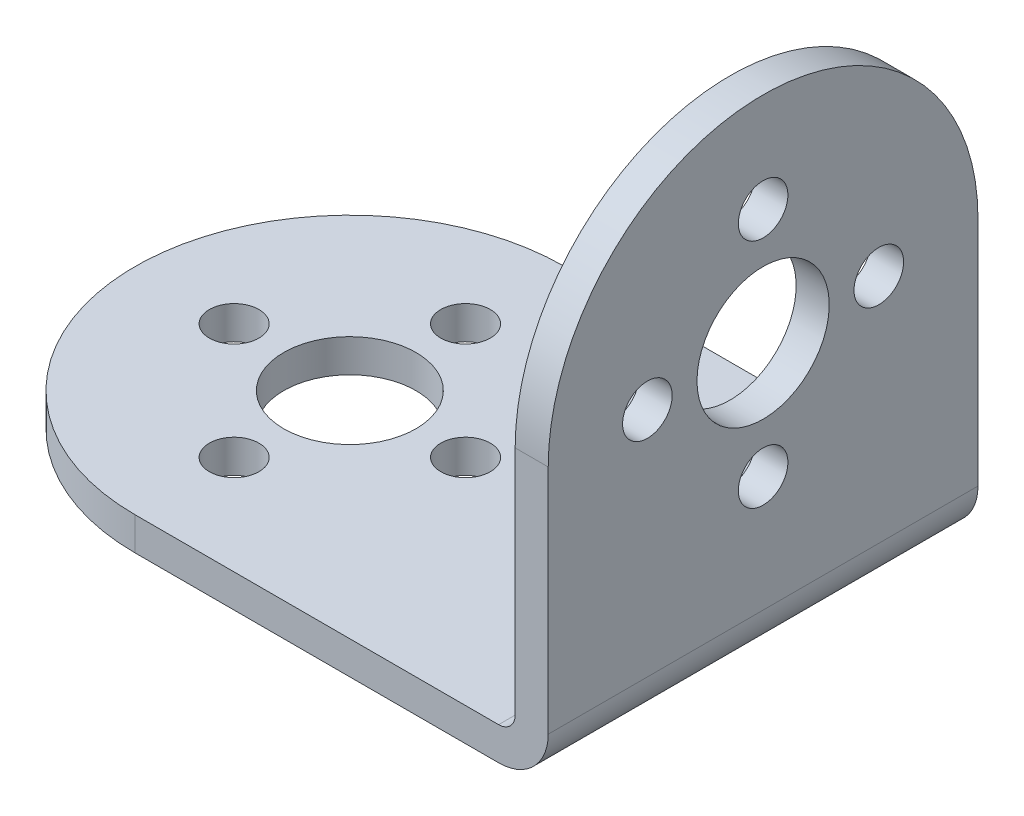
SolidWorks part; units mm, degrees
ref_plane "前视基准面" through (0, 0, 0) normal (0, 0, 1) x (1, 0, 0)
ref_plane "上视基准面" through (0, 0, 0) normal (0, 1, 0) x (1, 0, 0)
ref_plane "右视基准面" through (0, 0, 0) normal (1, 0, 0) x (0, 0, -1)
sketch "草图1" plane through (0, 0, 0) normal (0, 0, 1) x (1, 0, 0)
  line L1 (-19, -15) -> (19, -15)
  line L2 (-19, -15) -> (-19, -13)
  line L3 (17, 15) -> (19, 15)
  line L4 (19, -15) -> (19, 15)
  line L8 (17, -13) -> (17, 15)
  line L9 (17, -13) -> (-19, -13)
  point P0 (0, 0)
extrude "凸台-拉伸1" add sketch "草图1" along normal blind 26
fillet "圆角1" radius 1 1 edges at (17, -13, 13)
fillet "圆角2" radius 3 1 edges at (19, -15, 13)
sketch "草图2" plane through (17, 0, 0) normal (-1, 0, 0) x (0, 0, 1)
  line L1 (0, 2) -> (0, 15)
  line L2 (0, 15) -> (26, 15)
  line L3 (26, 15) -> (26, -12) construction
  line L4 (26, 15) -> (0, 15) construction
  line L5 (26, 15) -> (26, 2)
  arc A1 (26, 2) -> (0, 2) centre (13, 2) ccw
  circle A2 centre (13, 2) radius 4
  circle A4 centre (13, 9) radius 1.5
  circle A5 centre (20, 2) radius 1.5
  circle A6 centre (13, -5) radius 1.5
  circle A7 centre (6, 2) radius 1.5
  point P23 (13, 2)
  line M9 (0, 15) -> (0, -12)
  line M11 (26, -12) -> (26, 15)
  line M12 (26, 15) -> (0, 15)
  dimension "D1" = 4
extrude "切除-拉伸1" cut sketch "草图2" against normal blind 26 contours A1 M11 M12 | A1 L2 M9 | A7 | A4 | A6 | A5 | A2
sketch "草图3" plane through (0, -13, 0) normal (0, 1, 0) x (1, 0, 0)
  line L1 (-6, 0) -> (-19, 0)
  line L2 (-19, 0) -> (-19, -26)
  line L3 (-19, -26) -> (-6, -26)
  arc A1 (-6, 0) -> (-6, -26) centre (-6, -13) ccw
  circle A2 centre (-6, -13) radius 4
  circle A4 centre (-13, -13) radius 1.5
  circle A5 centre (-6, -6) radius 1.5
  circle A6 centre (1, -13) radius 1.5
  circle A7 centre (-6, -20) radius 1.5
  point P15 (-6, -13)
  line M6 (-19, -26) -> (16, -26)
  line M8 (16, 0) -> (-19, 0)
  line M9 (-19, 0) -> (-19, -26)
  dimension "D1" = 4
extrude "切除-拉伸2" cut sketch "草图3" against normal blind 26 contours A1 M8 M9 | A5 | A2 | A6 | A4 | A7 | A1 L2 M6
